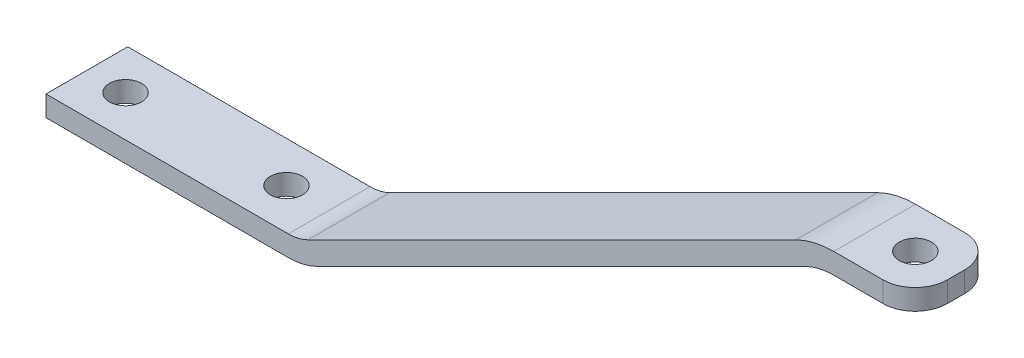
SolidWorks part; units mm, degrees
material "AISI 1020"
ref_plane "Plano superior" through (0, 0, 0) normal (0, 0, 1) x (1, 0, 0)
ref_plane "Plano frontal" through (0, 0, 0) normal (0, 1, 0) x (1, 0, 0)
ref_plane "Plano direito" through (0, 0, 0) normal (1, 0, 0) x (0, 0, -1)
sketch "Esboço1" plane through (0, 0, 0) normal (0, 0, 1) x (1, 0, 0)
  line L0 (0, 0) -> (37.6393, 0)
  line L1 (42.1115, 1.0557) -> (117.8885, 38.9443)
  line L2 (122.3607, 40) -> (135, 40)
  line L3 (0, 3.2) -> (37.6393, 3.2)
  line L4 (40.6804, 3.9179) -> (116.4575, 41.8064)
  line L5 (122.3607, 43.2) -> (135, 43.2)
  line L6 (135, 40) -> (135, 43.2)
  line L7 (0, 0) -> (0, 3.2)
  arc A0 (117.8885, 38.9443) -> (122.3607, 40) centre (122.3607, 30) cw
  arc A1 (42.1115, 1.0557) -> (37.6393, 0) centre (37.6393, 10) cw
  arc A2 (40.6804, 3.9179) -> (37.6393, 3.2) centre (37.6393, 10) cw
  arc A3 (116.4575, 41.8064) -> (122.3607, 43.2) centre (122.3607, 30) cw
  point P9 (120, 40)
  point P12 (40, 0)
  dimension "D5" = 10
  dimension "D1" = 40
  dimension "D2" = 80
  dimension "D3" = 15
  dimension "D4" = 40
  dimension "D6" = 37.6393
  dimension "D7" = 3.2
extrude "Ressalto-extrusão1" add sketch "Esboço1" along normal blind 12.7 contours L0 A1 L1 A0 L2 L6 L5 A3 L4 A2 L3 L7
sketch "Esboço2" plane through (0, 3.2, 0) normal (0, 1, 0) x (1, 0, 0)
  line L2 (0, -12.7) -> (0, 0) construction
  line L3 (0, -12.7) -> (37.6393, -12.7) construction
  circle A0 centre (6, -6.35) radius 2.5
  circle A1 centre (31, -6.35) radius 2.5
  dimension "D1" = 5
  dimension "D2" = 25
  dimension "D3" = 6
  dimension "D4" = 6.35
extrude "Corte-extrusão1" cut sketch "Esboço2" against normal through all
sketch "Esboço3" plane through (0, 43.2, 0) normal (0, 1, 0) x (1, 0, 0)
  line L0 (135, -6.35) -> (122.3607, -6.35) construction
  line L1 (135, -12.7) -> (135, 0) construction
  line L2 (128.6803, 0) -> (128.6803, -16.1183) construction
  line L3 (122.3607, 0) -> (135, 0) construction
  line L4 (122.3607, -12.7) -> (122.3607, 0) construction
  circle A0 centre (128.6803, -6.35) radius 2.5
  point P12 (128.6803, -6.35)
  dimension "D1" = 5
extrude "Corte-extrusão2" cut sketch "Esboço3" against normal through all
fillet "Filete1" radius 5 1 edges at (135, 41.6, 12.7)
fillet "Filete2" radius 5 1 edges at (135, 41.6, 0)
